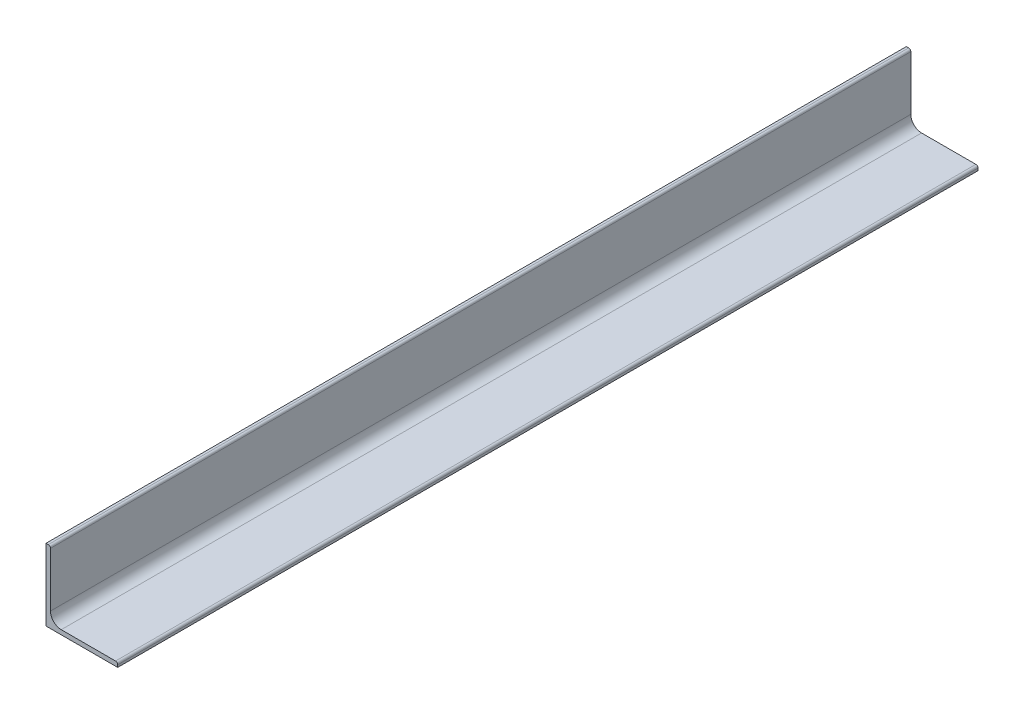
SolidWorks part; units mm, degrees
ref_plane "Front" through (0, 0, 0) normal (0, 0, 1) x (1, 0, 0)
ref_plane "Top" through (0, 0, 0) normal (0, 1, 0) x (1, 0, 0)
ref_plane "Right" through (0, 0, 0) normal (1, 0, 0) x (0, 0, -1)
sketch "Sketch1" plane through (0, 0, 0) normal (0, 0, 1) x (1, 0, 0)
  line L0 (0, 0) -> (0, 95.25)
  line L1 (0, 95.25) -> (-6.35, 95.25)
  line L2 (-6.35, 95.25) -> (-6.35, -6.35)
  line L3 (-6.35, -6.35) -> (95.25, -6.35)
  line L4 (95.25, -6.35) -> (95.25, 0)
  line L5 (95.25, 0) -> (0, 0)
sketch "Sketch2" plane through (0, 0, 0) normal (1, 0, 0) x (0, 0, -1)
  line L0 (-457.2, 0) -> (457.2, 0) construction
  point P2 (0, 0)
  dimension "Length" = 914.4
sketch "Sketch3" plane through (0, 0, 0) normal (0, 0, 1) x (1, 0, 0)
  line L0 (0, 0) -> (0, 95.25) construction
  line L1 (0, 95.25) -> (-6.35, 95.25) construction
  line L2 (-6.35, 95.25) -> (-6.35, -6.35) construction
  line L3 (-6.35, -6.35) -> (95.25, -6.35) construction
  line L4 (95.25, -6.35) -> (95.25, 0) construction
  line L5 (95.25, 0) -> (0, 0) construction
  line L6 (0, 15.24) -> (0, 92.202)
  line L7 (-3.048, 95.25) -> (-6.35, 95.25)
  line L8 (-6.35, 95.25) -> (-6.35, -5.334)
  line L9 (-5.334, -6.35) -> (95.25, -6.35)
  line L10 (95.25, -6.35) -> (95.25, -3.048)
  line L11 (92.202, 0) -> (15.24, 0)
  arc A0 (0, 15.24) -> (15.24, 0) centre (15.24, 15.24) ccw
  arc A1 (95.25, -3.048) -> (92.202, 0) centre (92.202, -3.048) ccw
  arc A2 (0, 92.202) -> (-3.048, 95.25) centre (-3.048, 92.202) ccw
  arc A3 (-6.35, -5.334) -> (-5.334, -6.35) centre (-5.334, -5.334) ccw
  dimension "D1" = 15.24
  dimension "D2" = 1.016
  dimension "D3" = 3.048
extrude "Boss-Extrude1" add sketch "Sketch3" along normal blind 1219.2
equation "\"D1@Sketch3\"=\"Height@Sketch1\"*.15"
equation "\"D2@Sketch3\"=\"Height@Sketch1\"*.01"
equation "\"D3@Sketch3\"=\"Height@Sketch1\"*.03"
